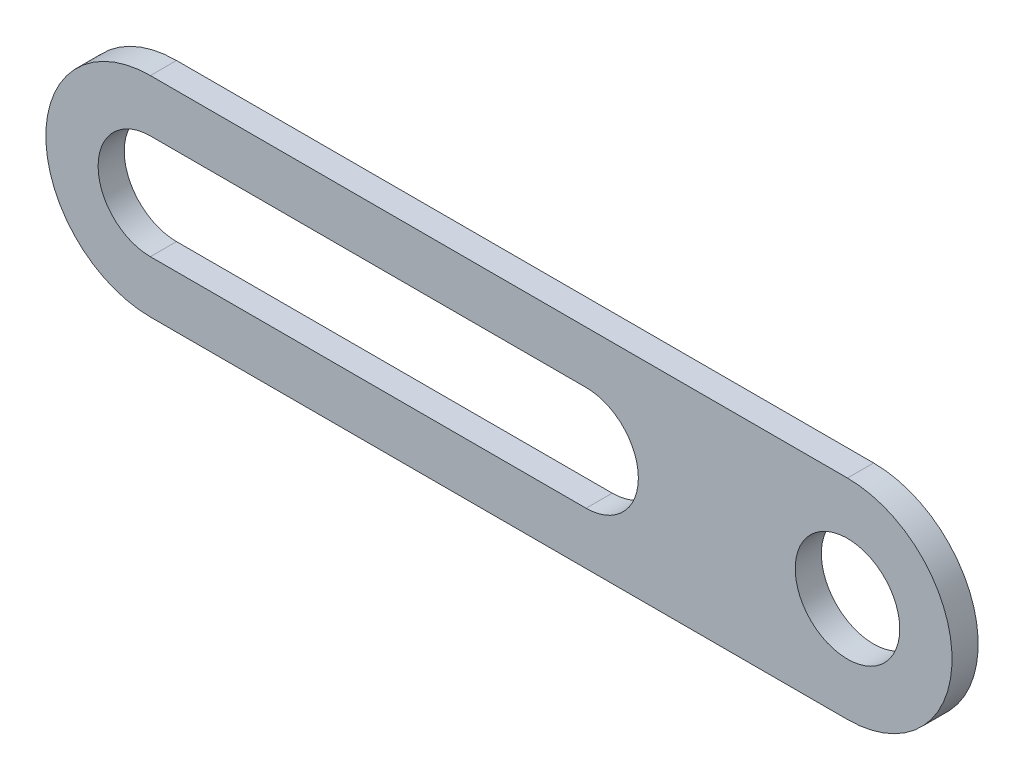
SolidWorks part; units mm, degrees
ref_plane "Front Plane" through (0, 0, 0) normal (0, 0, 1) x (1, 0, 0)
ref_plane "Top Plane" through (0, 0, 0) normal (0, 1, 0) x (1, 0, 0)
ref_plane "Right Plane" through (0, 0, 0) normal (1, 0, 0) x (0, 0, -1)
sketch "Sketch1" plane through (0, 0, 0) normal (0, 0, 1) x (1, 0, 0)
  line L0 (-69.375, 9.5625) -> (10.625, 9.5625)
  line L2 (10.625, -14.4375) -> (-69.375, -14.4375)
  line L4 (-69.375, 3.5625) -> (-19.375, 3.5625)
  line L5 (-69.375, -8.4375) -> (-19.375, -8.4375)
  arc A0 (-69.375, 9.5625) -> (-69.375, -14.4375) centre (-69.375, -2.4375) ccw
  arc A1 (10.625, -14.4375) -> (10.625, 9.5625) centre (10.625, -2.4375) ccw
  arc A2 (-69.375, 3.5625) -> (-69.375, -8.4375) centre (-69.375, -2.4375) ccw
  circle A3 centre (10.625, -2.4375) radius 6
  arc A4 (-19.375, 3.5625) -> (-19.375, -8.4375) centre (-19.375, -2.4375) cw
  dimension "D1" = 12
  dimension "D2" = 12
  dimension "D3" = 12
  dimension "D4" = 80
  dimension "D5" = 50
extrude "Boss-Extrude1" add sketch "Sketch1" along normal blind 3
